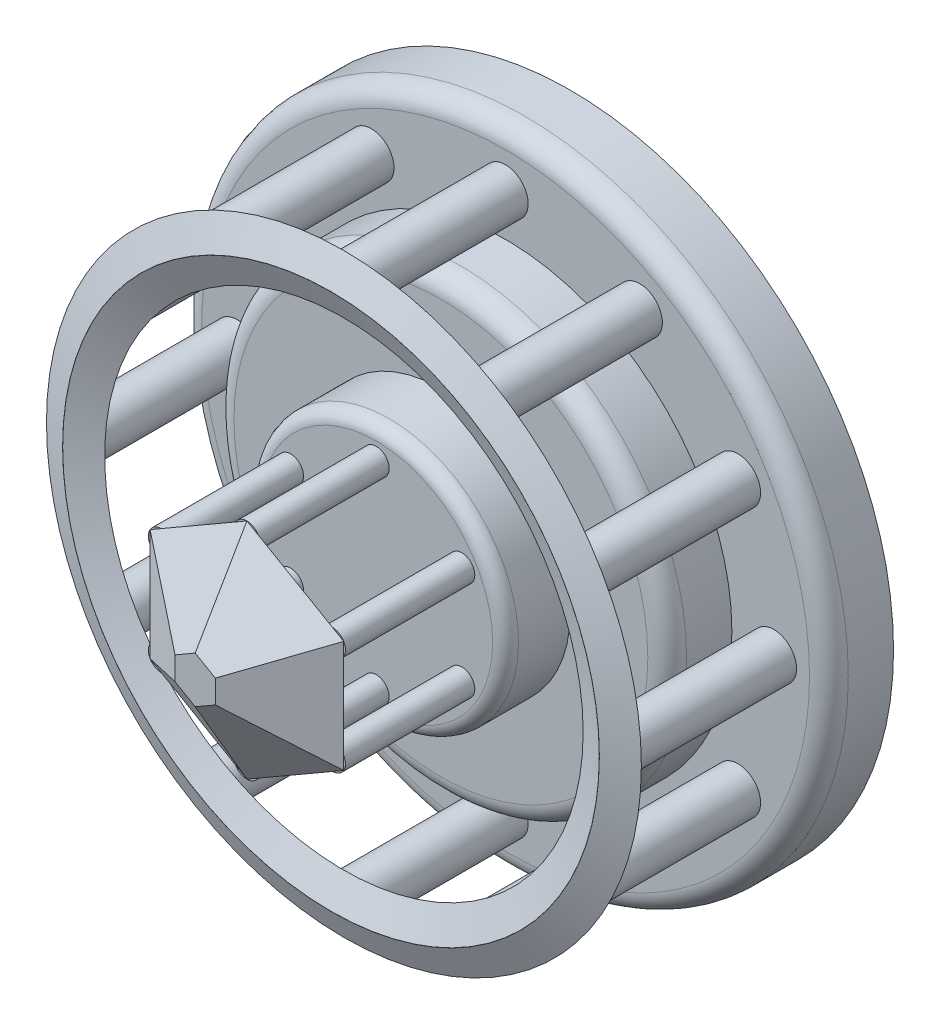
SolidWorks part; units mm, degrees
ref_plane "Přední rovina" through (0, 0, 0) normal (0, 0, 1) x (1, 0, 0)
ref_plane "Horní rovina" through (0, 0, 0) normal (0, 1, 0) x (1, 0, 0)
ref_plane "Pravá rovina" through (0, 0, 0) normal (1, 0, 0) x (0, 0, -1)
sketch "Skica12" plane through (0, 0, 0) normal (0, 0, 1) x (1, 0, 0)
  line L0 (0, 0) -> (-500, 0) construction
  circle A0 centre (0, 0) radius 500
  dimension "D1" = 500
extrude "Přidat vysunutím7" add sketch "Skica12" along normal blind 100
sketch "Skica13" plane through (0, 0, 100) normal (0, 0, 1) x (1, 0, 0)
  circle A0 centre (0, 0) radius 350
extrude "Přidat vysunutím8" add sketch "Skica13" along normal blind 100
sketch "Skica14" plane through (0, 0, 200) normal (0, 0, 1) x (1, 0, 0)
  circle A0 centre (0, 0) radius 200
extrude "Přidat vysunutím9" add sketch "Skica14" along normal blind 100
sketch "Skica15" plane through (0, 0, 300) normal (0, 0, 1) x (1, 0, 0)
  line L0 (0, 0) -> (0, 200) construction
  circle A0 centre (0, 0) radius 200 construction
  circle A2 centre (0, 152.8975) radius 20
  circle A3 centre (132.4132, 76.4488) radius 20
  circle A4 centre (132.4132, -76.4488) radius 20
  circle A5 centre (0, -152.8975) radius 20
  circle A6 centre (-132.4132, -76.4488) radius 20
  circle A7 centre (-132.4132, 76.4488) radius 20
extrude "Přidat vysunutím10" add sketch "Skica15" along normal blind 200
sketch "Skica16" plane through (0, 0, 500) normal (0, 0, 1) x (1, 0, 0)
  line L1 (-149.7335, -86.4491) -> (0.0004, -172.8975)
  line L2 (0.0004, -172.8975) -> (149.7339, -86.4484)
  line L3 (149.7339, -86.4484) -> (149.7335, 86.4491)
  line L4 (149.7335, 86.4491) -> (-0.0004, 172.8975)
  line L5 (-0.0004, 172.8975) -> (-149.7339, 86.4484)
  line L6 (-149.7339, 86.4484) -> (-149.7335, -86.4491)
  circle A0 centre (0, 0) radius 149.7337 construction
extrude "Přidat vysunutím11" add sketch "Skica16" along normal blind 80 draft 56
fillet "Zaoblit3" radius 30 1 edges at (500, 0, 100)
fillet "Zaoblit4" radius 30 1 edges at (350, 0, 200)
fillet "Zaoblit5" radius 20 1 edges at (200, 0, 300)
sketch "Skica21" plane through (0, 0, 100) normal (0, 0, 1) x (1, 0, 0)
  circle A3 centre (0, 415) radius 35
  circle A4 centre (207.5, 359.4005) radius 35
  circle A5 centre (359.4005, 207.5) radius 35
  circle A6 centre (415, 0) radius 35
  circle A7 centre (359.4005, -207.5) radius 35
  circle A8 centre (207.5, -359.4005) radius 35
  circle A9 centre (0, -415) radius 35
  circle A10 centre (-207.5, -359.4005) radius 35
  circle A11 centre (-359.4005, -207.5) radius 35
  circle A12 centre (-415, 0) radius 35
  circle A13 centre (-359.4005, 207.5) radius 35
  circle A14 centre (-207.5, 359.4005) radius 35
extrude "Přidat vysunutím12" add sketch "Skica21" along normal blind 250
sketch "Skica22" plane through (0, 0, 350) normal (0, 0, 1) x (1, 0, 0)
  circle A0 centre (0, 0) radius 460
  circle A2 centre (0, 0) radius 370
  point P3 (0, 0)
  point P4 (0, 0)
  dimension "D1" = 90
extrude "Přidat vysunutím13" add sketch "Skica22" along normal blind 20 draft 66 contours A2 | A0
